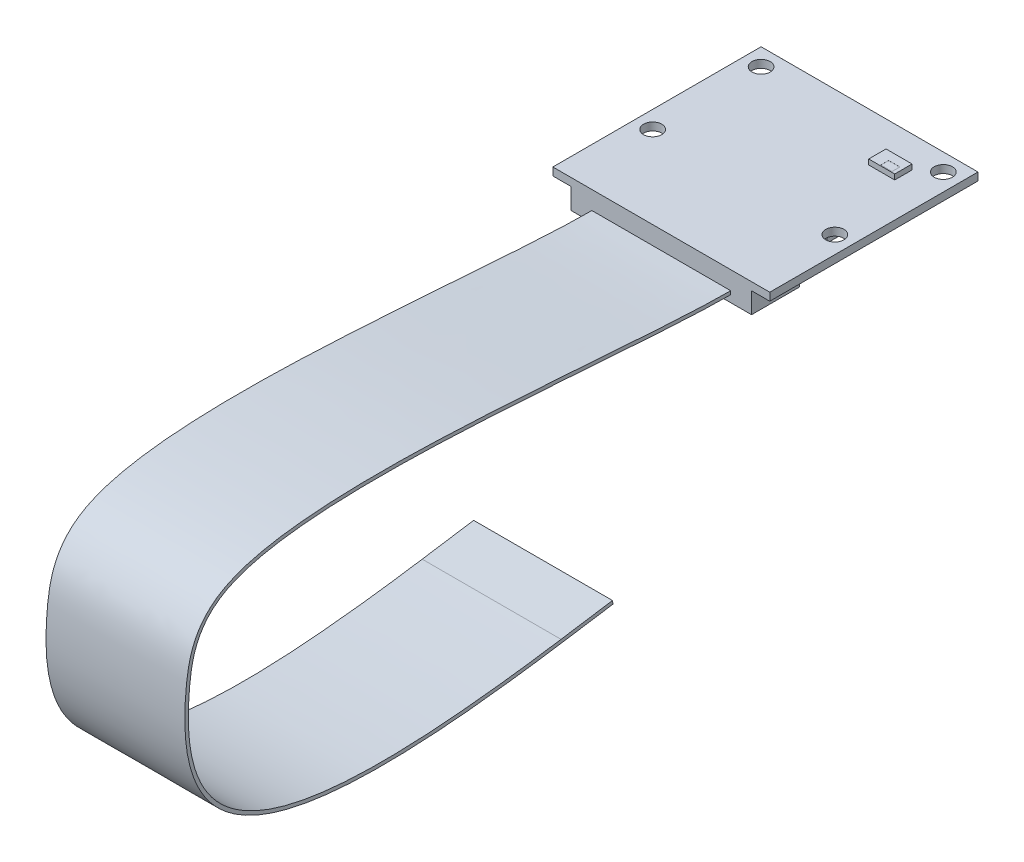
SolidWorks part; units mm, degrees
material "Epoxid, Ungefüllt"
ref_plane "Vorne" through (0, 0, 0) normal (0, 0, 1) x (1, 0, 0)
ref_plane "Oben" through (0, 0, 0) normal (0, 1, 0) x (1, 0, 0)
ref_plane "Rechts" through (0, 0, 0) normal (1, 0, 0) x (0, 0, -1)
sketch "Skizze1" plane through (0, 0, 0) normal (0, 1, 0) x (1, 0, 0)
  line L0 (0, 14.5) -> (0, -9.5) construction
  line L1 (-12.5, 14.5) -> (12.5, 14.5)
  line L2 (-12.5, 14.5) -> (-12.5, -9.5)
  line L3 (-12.5, -9.5) -> (12.5, -9.5)
  line L4 (12.5, 14.5) -> (12.5, -9.5)
  dimension "D1" = 24
  dimension "D2" = 25
  dimension "D3" = 9.5
extrude "PCB" add sketch "Skizze1" against normal blind 0.9
sketch "Skizze2" plane through (0, 0, 0) normal (0, 1, 0) x (1, 0, 0)
  line L0 (12.5, 14.5) -> (-12.5, 14.5) construction
  line L1 (12.5, -9.5) -> (12.5, 14.5) construction
  line L2 (0, 0) -> (0, 9.3158) construction
  circle A0 centre (10.5, 12.5) radius 1.05
  circle A1 centre (10.5, 0) radius 1.05
  circle A2 centre (-10.5, 0) radius 1.05
  circle A3 centre (-10.5, 12.5) radius 1.05
  dimension "D1" = 2.1
  dimension "D2" = 2
  dimension "D3" = 2
  dimension "D4" = 12.5
extrude "Mounting_Holes" cut sketch "Skizze2" against normal through all
sketch "Skizze3" plane through (0, -0.9, 0) normal (0, -1, 0) x (1, 0, 0)
  line L0 (0, 4) -> (0, 0) construction
  line L1 (-10.4, 9.5) -> (10.4, 9.5)
  line L2 (-10.4, 9.5) -> (-10.4, 4)
  line L3 (-10.4, 4) -> (10.4, 4)
  line L4 (10.4, 9.5) -> (10.4, 4)
  line L5 (-12.5, 9.5) -> (12.5, 9.5) construction
  dimension "D1" = 20.8
  dimension "D2" = 5.5
extrude "Connector_closed" add sketch "Skizze3" along normal blind 2.4
sketch "Skizze4" plane through (0, -0.9, 0) normal (0, -1, 0) x (1, 0, 0)
  line L0 (-12.5, -14.5) -> (-12.5, 9.5) construction
  line L1 (-9, -0.9) -> (8.7, -0.9)
  line L2 (-9, -0.9) -> (-9, -12.5)
  line L3 (-9, -12.5) -> (8.7, -12.5)
  line L4 (8.7, -0.9) -> (8.7, -12.5)
  line L5 (12.5, -14.5) -> (-12.5, -14.5) construction
  dimension "D1" = 17.7
  dimension "D2" = 3.5
  dimension "D3" = 2
  dimension "D4" = 13.6
extrude "Components_worst-case_Boundary-Box" add sketch "Skizze4" along normal blind 1.3
sketch "Skizze5" plane through (0, 0, 0) normal (1, 0, 0) x (0, 0, -1)
  line L0 (-9.5, -3.3) -> (-9.5, -0.9) construction
  line L1 (-9.5, 0) -> (14.5, 0) construction
  line L2 (-19.1541, -2.1) -> (0.1541, -2.1) construction
  line L3 (-28.9969, -27.5148) -> (-23.0666, -26.6025)
  spline S0 degree 3 poles (-9.5, -2.1) (-22.9784, -2.1) (-69.5026, 4.5681) (-76.0904, -27.5225) (-60.9351, -32.4284) (-28.9969, -27.5148) knots 0 0 0 0 0.278118 0.378118 1 1 1 1
  dimension "D1" = 2.1
  dimension "D2" = 6
sketch "Skizze6" plane through (0, 0, 9.5) normal (0, 0, 1) x (1, 0, 0)
  line L1 (-8, -2.1) -> (8, -2.1)
  line L2 (-8, -2.1) -> (-8, -2.5)
  line L3 (-8, -2.5) -> (8, -2.5)
  line L4 (8, -2.1) -> (8, -2.5)
  dimension "D1" = 16
  dimension "D2" = 0.4
sweep "Cable_156mm_free_Length" add profiles "Skizze6" path "Skizze5"
sketch "Skizze7" plane through (0, 0, 0) normal (0, 1, 0) x (1, 0, 0)
  line L0 (12.5, 14.5) -> (-12.5, 14.5) construction
  line L1 (5.5, 10.9) -> (8.5, 10.9)
  line L2 (5.5, 10.9) -> (5.5, 8.9)
  line L3 (5.5, 8.9) -> (8.5, 8.9)
  line L4 (8.5, 10.9) -> (8.5, 8.9)
  line L5 (12.5, -9.5) -> (12.5, 14.5) construction
  dimension "D1" = 5.6
  dimension "D2" = 3.6
  dimension "D3" = 4
  dimension "D4" = 7
extrude "Components_worst-case_Boundary-Box2" add sketch "Skizze7" along normal blind 0.6
sketch "Skizze8" plane through (0, 0.6, 0) normal (0, 1, 0) x (1, 0, 0)
  line L0 (12.5, -9.5) -> (12.5, 14.5) construction
  line L1 (8.1, 9) -> (6.8, 9)
  line L2 (8.1, 9) -> (8.1, 9.9)
  line L3 (8.1, 9.9) -> (6.8, 9.9)
  line L4 (6.8, 9) -> (6.8, 9.9)
  line L5 (12.5, 14.5) -> (-12.5, 14.5) construction
  dimension "D1" = 1.3
  dimension "D2" = 0.9
  dimension "D3" = 4.4
  dimension "D4" = 4.6
extrude "Status_LED" cut sketch "Skizze8" against normal blind 0.01
